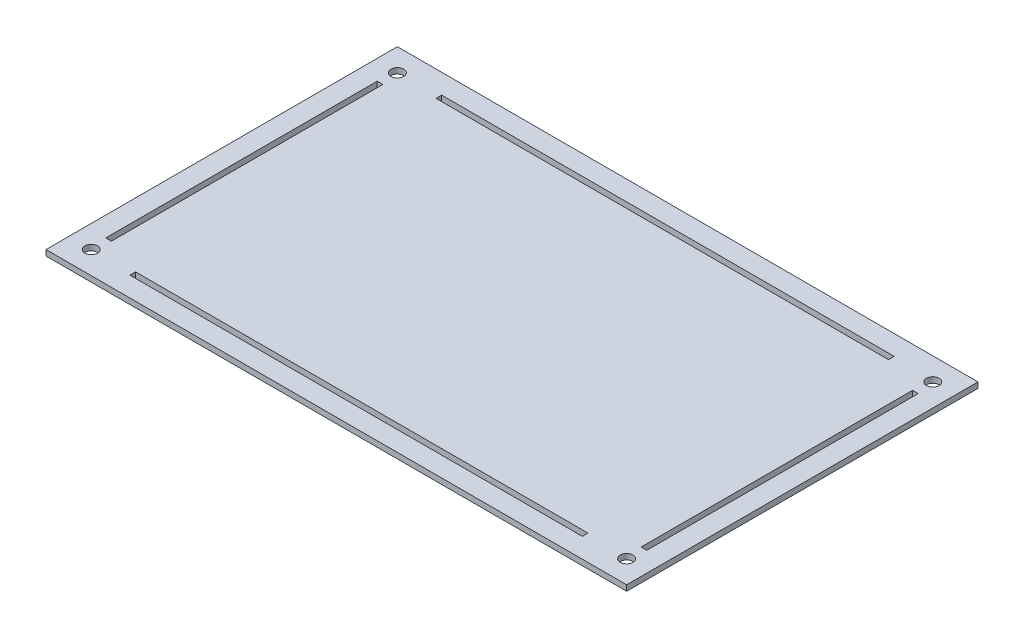
SolidWorks part; units mm, degrees
ref_plane "Front Plane" through (0, 0, 0) normal (0, 0, 1) x (1, 0, 0)
ref_plane "Top Plane" through (0, 0, 0) normal (0, 1, 0) x (1, 0, 0)
ref_plane "Right Plane" through (0, 0, 0) normal (1, 0, 0) x (0, 0, -1)
sketch "Sketch1" plane through (0, 0, 0) normal (0, 1, 0) x (1, 0, 0)
  line L1 (-150.2918, 85.9396) -> (150.2918, 85.9396) construction
  line L2 (-150.2918, 85.9396) -> (-150.2918, -85.9396) construction
  line L3 (-150.2918, -85.9396) -> (150.2918, -85.9396) construction
  line L4 (150.2918, 85.9396) -> (150.2918, -85.9396) construction
  line L5 (-150.2918, 85.9396) -> (150.2918, -85.9396) construction
  line L6 (-150.2918, -85.9396) -> (150.2918, 85.9396) construction
  line L7 (-162.9918, 98.6396) -> (162.9918, 98.6396)
  line L8 (-162.9918, 98.6396) -> (-162.9918, -98.6396)
  line L9 (-162.9918, -98.6396) -> (162.9918, -98.6396)
  line L10 (162.9918, 98.6396) -> (162.9918, -98.6396)
  line L11 (-162.9918, 98.6396) -> (162.9918, -98.6396) construction
  line L12 (-162.9918, -98.6396) -> (162.9918, 98.6396) construction
  point P4 (0, 0)
  point P5 (0, 0)
  point P11 (0, 0)
  dimension "D1" = 300.5836
  dimension "D2" = 171.8793
  dimension "D3" = 12.7
  dimension "D4" = 12.7
extrude "Boss-Extrude1" add sketch "Sketch1" along normal blind 3.175
hole_wizard "1/4 Clearance Hole1" positions "Sketch2" profile "Sketch3" hole size "1/4" standard "ANSI Inch" end condition through all
sketch "Sketch2" plane through (0, 3.175, 0) normal (0, 1, 0) x (1, 0, 0)
  point P0 (-150.2918, 85.9396)
  point P3 (150.2918, 85.9396)
  point P6 (150.2918, -85.9396)
  point P9 (-150.2918, -85.9396)
sketch "Sketch3" plane through (-150.2918, 3.175, -85.9396) normal (1, 0, 0) x (0, 0, 1)
  line L0 (0, 0) -> (0, 3.175)
  line L1 (0, 3.175) -> (3.5712, 3.175)
  line L2 (3.5712, 3.175) -> (3.5712, 0)
  line L5 (3.5712, 0) -> (0, 0)
  line L11 (0, -6.35) -> (0, 107.95) construction
  dimension "Thru Hole Dia." = 7.1425
  dimension "Thru Hole Depth" = 3.175
sketch "Sketch4" plane through (0, 3.175, 0) normal (0, 1, 0) x (1, 0, 0)
  line L0 (-150.2918, 85.9396) -> (-150.2918, -85.9396) construction
  line L1 (-151.8793, 76.2) -> (-148.7043, 76.2)
  line L2 (-151.8793, 76.2) -> (-151.8793, -76.2)
  line L3 (-151.8793, -76.2) -> (-148.7043, -76.2)
  line L4 (-148.7043, 76.2) -> (-148.7043, -76.2)
  line L5 (-151.8793, 76.2) -> (-148.7043, -76.2) construction
  line L6 (-151.8793, -76.2) -> (-148.7043, 76.2) construction
  line L7 (0, -1.7463) -> (0, 1.7463) construction
  line L8 (151.8793, -76.2) -> (148.7043, 76.2) construction
  line L9 (151.8793, 76.2) -> (148.7043, -76.2) construction
  line L10 (148.7043, 76.2) -> (148.7043, -76.2)
  line L11 (151.8793, -76.2) -> (148.7043, -76.2)
  line L12 (151.8793, 76.2) -> (151.8793, -76.2)
  line L13 (151.8793, 76.2) -> (148.7043, 76.2)
  line L14 (-150.2918, 85.9396) -> (150.2918, 85.9396) construction
  line L15 (-127, 87.5271) -> (127, 87.5271)
  line L16 (-127, 87.5271) -> (-127, 84.3521)
  line L17 (-127, 84.3521) -> (127, 84.3521)
  line L18 (127, 87.5271) -> (127, 84.3521)
  line L19 (-127, 87.5271) -> (127, 84.3521) construction
  line L20 (-127, 84.3521) -> (127, 87.5271) construction
  line L21 (-1.7463, 0) -> (1.7463, 0) construction
  line L22 (-127, -84.3521) -> (127, -87.5271) construction
  line L23 (-127, -87.5271) -> (127, -84.3521) construction
  line L24 (127, -87.5271) -> (127, -84.3521)
  line L25 (-127, -84.3521) -> (127, -84.3521)
  line L26 (-127, -87.5271) -> (-127, -84.3521)
  line L27 (-127, -87.5271) -> (127, -87.5271)
  point P4 (-150.2918, 0)
  point P5 (0, 0)
  point P14 (150.2918, 0)
  point P19 (0, 85.9396)
  point P28 (0, -85.9396)
  dimension "D1" = 3.175
  dimension "D2" = 152.4
  dimension "D3" = 3.175
  dimension "D4" = 254
extrude "Cut-Extrude1" cut sketch "Sketch4" against normal through all
equation "\"width\"= 6.7669in"
equation "\"length\"= 11.834in"
equation "\"D1@Sketch1\"=\"length\""
equation "\"D2@Sketch1\"=\"width\""
equation "\"Side Thickness\"= 0.125in"
equation "\"D1@Sketch4\"=\"Side Thickness\""
equation "\"D3@Sketch4\"=\"Side Thickness\""
